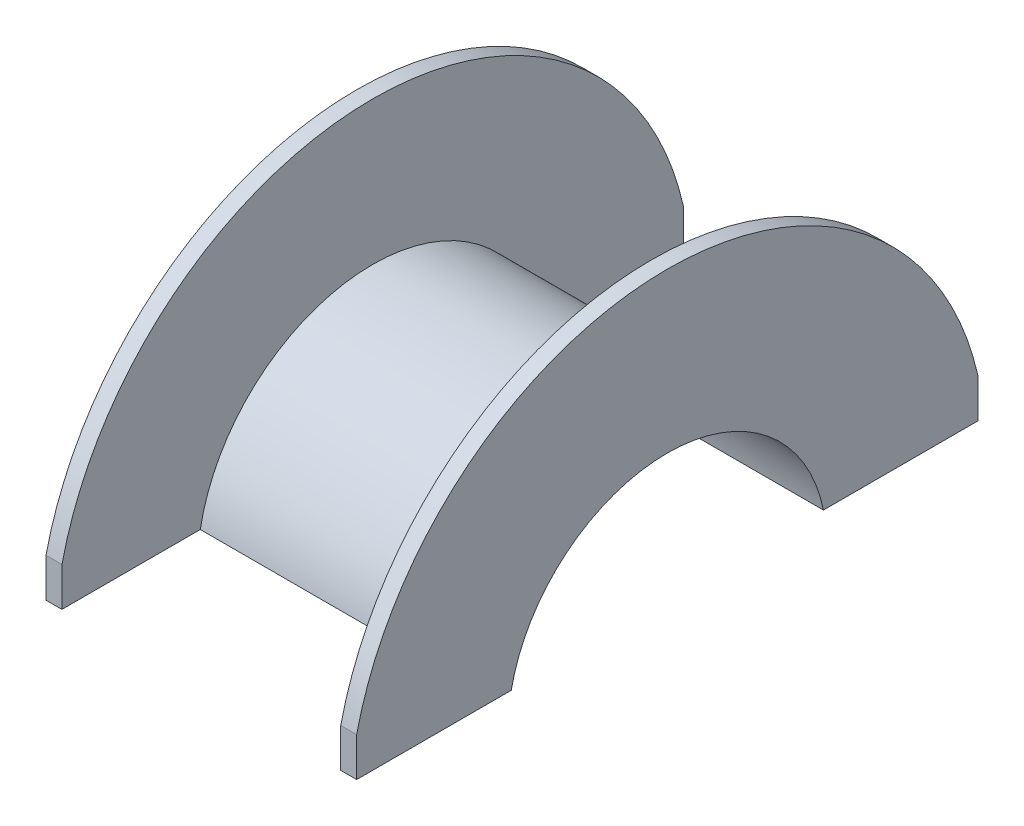
SolidWorks part; units mm, degrees
ref_plane "Спереди" through (0, 0, 0) normal (0, 0, 1) x (1, 0, 0)
ref_plane "Сверху" through (0, 0, 0) normal (0, 1, 0) x (1, 0, 0)
ref_plane "Справа" through (0, 0, 0) normal (1, 0, 0) x (0, 0, -1)
sketch "Эскиз1" plane through (0, 0, 0) normal (0, 0, 1) x (1, 0, 0)
  line L0 (-17.3367, 0) -> (21.9599, 0) construction
  line L2 (-9.75, 20) -> (-8.75, 20)
  line L3 (-9.75, 20) -> (-9.75, 10)
  line L4 (-9.75, 10) -> (9.75, 10)
  line L5 (9.75, 20) -> (9.75, 10)
  line L6 (-8.75, 20) -> (-8.75, 11)
  line L7 (-8.75, 11) -> (8.75, 11)
  line L8 (8.75, 11) -> (8.75, 20)
  line L9 (8.75, 20) -> (9.75, 20)
  dimension "D1" = 10
  dimension "D2" = 19.5
  dimension "D3" = 1
  dimension "D4" = 1
  dimension "D5" = 1
  dimension "D6" = 20
revolve "Повернуть1" add sketch "Эскиз1" angle 360 about L0
sketch "Эскиз2" plane through (9.75, 0, 0) normal (1, 0, 0) x (0, 0, -1)
  line L1 (-26.9172, -28.1234) -> (24.1584, -28.1234)
  line L2 (-26.9172, -28.1234) -> (-26.9172, 2)
  line L3 (-26.9172, 2) -> (24.1584, 2)
  line L4 (24.1584, -28.1234) -> (24.1584, 2)
  circle A1 centre (0, 0) radius 20 construction
  dimension "D1" = 18
extrude "Вырез-Вытянуть1" cut sketch "Эскиз2" against normal blind 40
sketch "Эскиз3" plane through (9.75, 0, 0) normal (1, 0, 0) x (0, 0, -1)
  line L0 (0, 0) -> (0, 15.3537) construction
  line L1 (-21.8415, -1.4758) -> (-19.5, -1.4758)
  line L2 (-21.8415, -1.4758) -> (-21.8415, 6.5731)
  line L3 (-21.8415, 6.5731) -> (-19.5, 6.5731)
  line L4 (-19.5, -1.4758) -> (-19.5, 6.5731)
  line L5 (19.5, -1.11) -> (21.2561, -1.11)
  line L6 (19.5, -1.11) -> (19.5, 5.7316)
  line L7 (19.5, 5.7316) -> (21.2561, 5.7316)
  line L8 (21.2561, -1.11) -> (21.2561, 5.7316)
  dimension "D1" = 19.5
extrude "Вырез-Вытянуть2" cut sketch "Эскиз3" against normal blind 20
